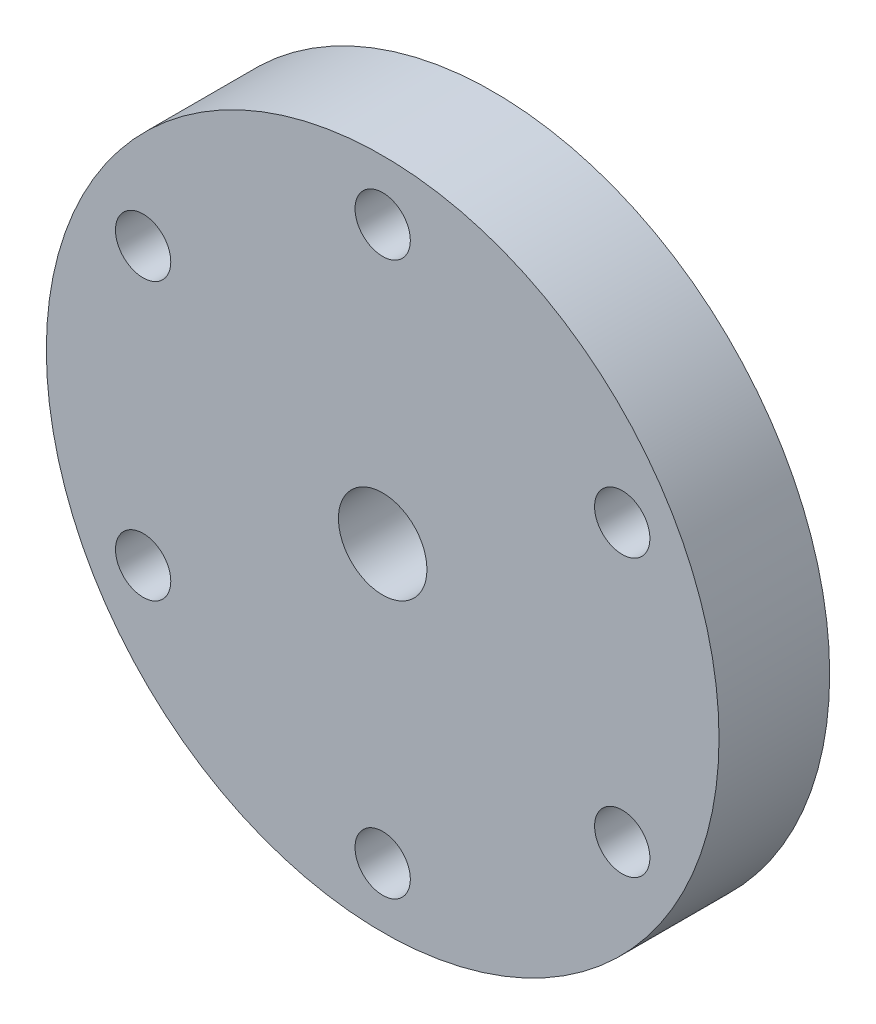
SolidWorks part; units mm, degrees
ref_plane "前视基准面" through (0, 0, 0) normal (0, 0, 1) x (1, 0, 0)
ref_plane "上视基准面" through (0, 0, 0) normal (0, 1, 0) x (1, 0, 0)
ref_plane "右视基准面" through (0, 0, 0) normal (1, 0, 0) x (0, 0, -1)
sketch "草图1" plane through (0, 0, 0) normal (0, 0, 1) x (1, 0, 0)
  circle A0 centre (0, 0) radius 15.2
  dimension "D1" = 30.4
extrude "凸台-拉伸2" add sketch "草图1" along normal blind 5
sketch "草图3" plane through (0, 0, 5) normal (0, 0, 1) x (1, 0, 0)
  line L0 (0, 12.5) -> (0, -25.0226) construction
  circle A0 centre (0, 0) radius 12.5 construction
  circle A1 centre (0, 12.5) radius 1.25
  circle A2 centre (10.8253, 6.25) radius 1.25
  circle A3 centre (10.8253, -6.25) radius 1.25
  circle A4 centre (0, -12.5) radius 1.25
  circle A5 centre (-10.8253, -6.25) radius 1.25
  circle A6 centre (-10.8253, 6.25) radius 1.25
  point P19 (0, 0)
  dimension "D1" = 25
  dimension "D2" = 2.5
  dimension "D3" = 6
sketch "草图4" plane through (0, 0, 5) normal (0, 0, 1) x (1, 0, 0)
  circle A0 centre (0, 0) radius 2
  dimension "D1" = 4
sketch "草图5" plane through (0, 0, 0) normal (0, 0, -1) x (-1, 0, 0)
  circle A0 centre (0, 0) radius 2.5
  dimension "D1" = 5
extrude "切除-拉伸1" cut sketch "草图3" against normal through all both and the other way through all
extrude "切除-拉伸2" cut sketch "草图4" against normal through all both and the other way through all
